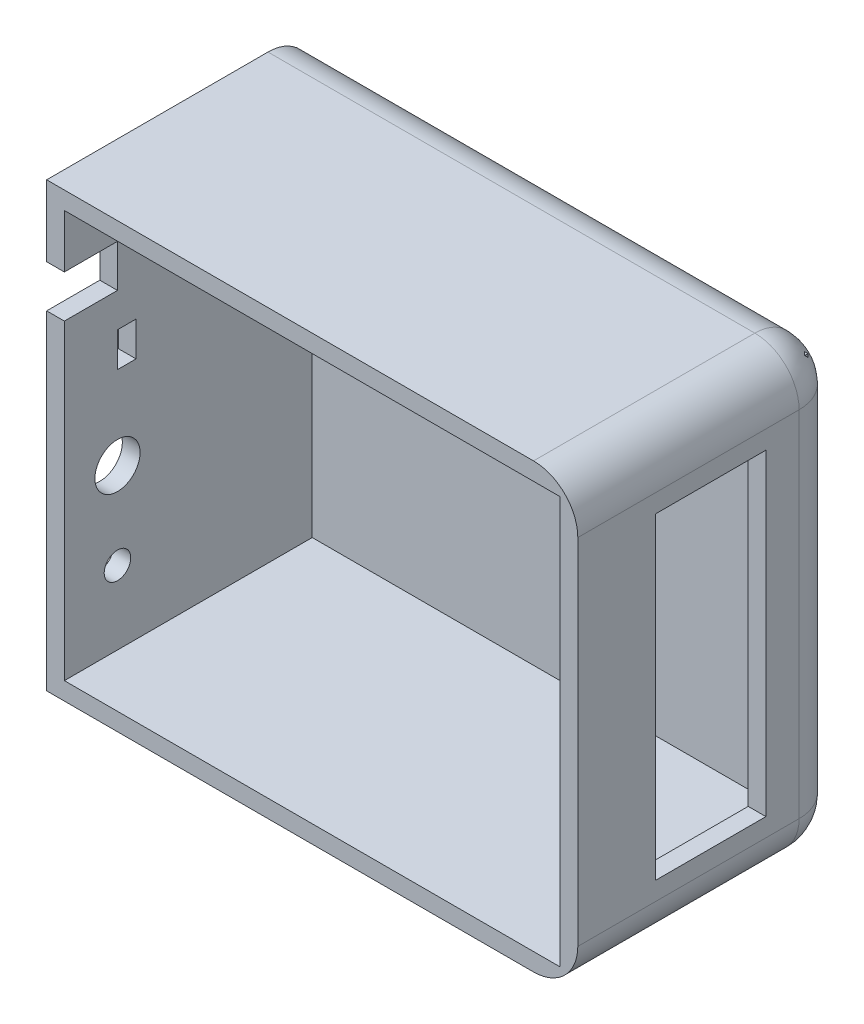
SolidWorks part; units mm, degrees
ref_plane "Plano frontal" through (0, 0, 0) normal (0, 0, 1) x (1, 0, 0)
ref_plane "Plano superior" through (0, 0, 0) normal (0, 1, 0) x (1, 0, 0)
ref_plane "Plano direito" through (0, 0, 0) normal (1, 0, 0) x (0, 0, -1)
sketch "Esboço1" plane through (0, 0, 0) normal (0, 0, 1) x (1, 0, 0)
  line L1 (0, 0) -> (120, 0)
  line L2 (0, 0) -> (0, 100)
  line L3 (0, 100) -> (120, 100)
  line L4 (120, 0) -> (120, 100)
  dimension "D1" = 100
  dimension "D2" = 120
extrude "Ressalto-extrusão1" add sketch "Esboço1" along normal blind 4
sketch "Esboço2" plane through (0, 0, 0) normal (0, 0, 1) x (1, 0, 0)
  line L0 (120, 0) -> (120, 100) construction
  line L1 (0, 100) -> (120, 100)
  line L2 (0, 100) -> (0, 96)
  line L3 (0, 96) -> (120, 96)
  line L4 (120, 100) -> (120, 96)
  line L5 (0, 0) -> (120, 0) construction
  line L6 (0, 100) -> (4, 100)
  line L7 (0, 100) -> (0, 0)
  line L8 (0, 0) -> (4, 0)
  line L9 (4, 100) -> (4, 0)
  line L11 (120, 100) -> (116, 100)
  line L12 (120, 100) -> (120, 0)
  line L13 (120, 0) -> (116, 0)
  line L14 (116, 100) -> (116, 0)
  line L15 (0, 4) -> (120, 4)
  line L16 (0, 4) -> (0, 0)
  line L17 (0, 0) -> (120, 0)
  line L18 (120, 4) -> (120, 0)
  dimension "D1" = 4
  dimension "D2" = 4
  dimension "D3" = 4
  dimension "D4" = 4
extrude "Ressalto-extrusão2" add sketch "Esboço2" along direction (0, 0, -1) on the side of the normal blind 60 contours L9 L1 L2 L3 | L1 L14 L3 L4 | L14 L1 L9 L3 | L14 L15 L12 L3 | L15 L14 L13 L12 | L9 L17 L14 L15 | L15 L7 L8 L9 | L7 L15 L9 L3
sketch3d "3DSketch1"
  line L2 (120, 100, 60) -> (120, 0, 0) construction
  line L3 (120, 0, 0) -> (120, 0, 60) construction
  line L4 (120, 0, 60) -> (120, 100, 0) construction
  line L6 (120, 14.15, 17.5) -> (120, 14.15, 42.5)
  line L7 (120, 14.15, 17.5) -> (120, 85.85, 17.5)
  line L8 (120, 85.85, 17.5) -> (120, 85.85, 42.5)
  line L9 (120, 14.15, 42.5) -> (120, 85.85, 42.5)
  line L10 (120, 14.15, 17.5) -> (120, 85.85, 42.5) construction
  line L11 (120, 85.85, 17.5) -> (120, 14.15, 42.5) construction
  point P8 (120, 50, 30)
  dimension "D1" = 71.7
  dimension "D2" = 25
extrude "Corte-extrusão1" cut sketch "3DSketch1" along direction (-1, 0, 0) on the side of the normal blind 26 and the other way blind 23
fillet "Filete1" radius 10 1 edges at (120, 50, 0)
fillet "Filete2" radius 10 3 edges at (120, 0, 35) (117.0711, 0, 2.9289) (55, 0, 0)
fillet "Filete3" radius 10 3 edges at (120, 100, 35) (117.0711, 100, 2.9289) (55, 100, 0)
sketch3d "3DSketch2"
  line L0 (0, 100, 60) -> (0, 0, 60) construction
  line L1 (0, 83.9579, 60) -> (0, 83.9579, 48)
  line L2 (0, 83.9579, 60) -> (0, 74.3579, 60)
  line L3 (0, 74.3579, 60) -> (0, 74.3579, 48)
  line L4 (0, 83.9579, 48) -> (0, 74.3579, 48)
  line L5 (0, 74.3579, 60) -> (0, 74.3579, 48) construction
  line L6 (0, 74.3579, 48) -> (0, 66.6579, 48) construction
  line L8 (0, 66.6579, 48) -> (0, 66.6579, 43.8)
  line L9 (0, 66.6579, 48) -> (0, 58.8579, 48)
  line L10 (0, 58.8579, 48) -> (0, 58.8579, 43.8)
  line L11 (0, 66.6579, 43.8) -> (0, 58.8579, 43.8)
  dimension "D1" = 9.6
  dimension "D2" = 12
  dimension "D3" = 7.7
  dimension "D4" = 7.8
  dimension "D5" = 4.2
extrude "Corte-extrusão2" cut sketch "3DSketch2" along direction (1, 0, 0) on the side of the normal blind 37 and the other way blind 36 contours L1 L4 L3 L2 | L9 L10 L11 L8
sketch3d "3DSketch3"
  line L0 (0, 58.8579, 43.8) -> (0, 0, 43.8) construction
  line L1 (0, 0, 60) -> (0, 0, 10) construction
  line L2 (0, 0, 43.8) -> (0, 58.8579, 48) construction
  line L3 (0, 58.8579, 48) -> (0, 0, 48) construction
  circle A0 centre (0, 40.0942, 48) radius 5.1
  circle A1 centre (0, 20.5603, 48) radius 3
  point P10 (5.1, 40.0942, 48)
  point P13 (3, 20.5603, 48)
  dimension "D1" = 10.2
  dimension "D2" = 6
extrude "Corte-extrusão3" cut sketch "3DSketch3" along direction (1, 0, 0) on the side of the normal blind 28 and the other way blind 18 contours A0 | A1
